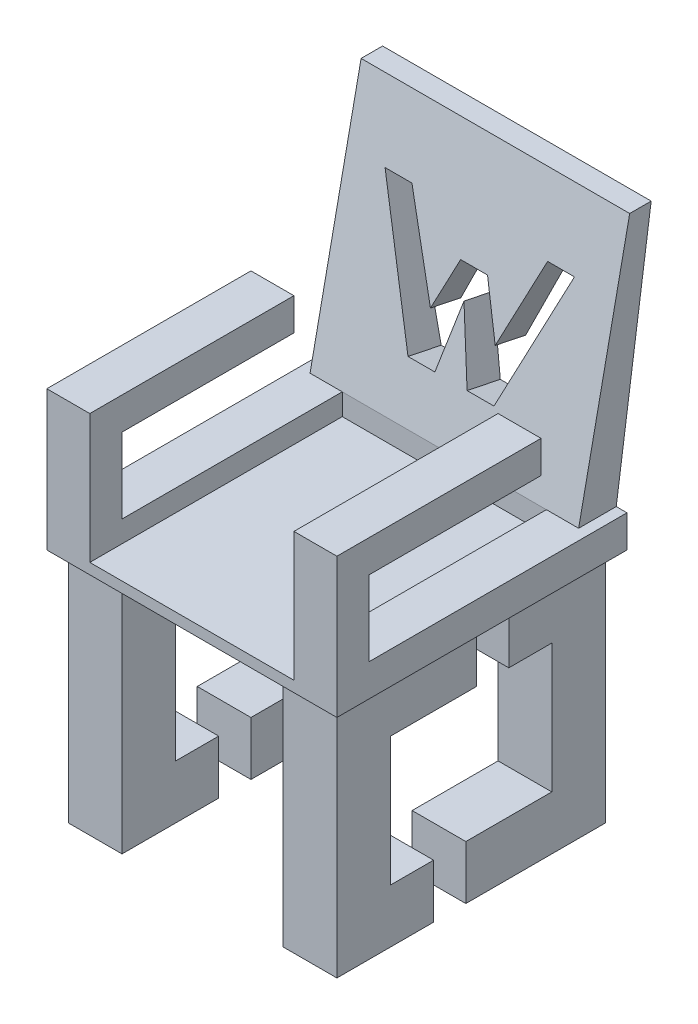
SolidWorks part; units mm, degrees
ref_plane "Front Plane" through (0, 0, 0) normal (0, 0, 1) x (1, 0, 0)
ref_plane "Top Plane" through (0, 0, 0) normal (0, 1, 0) x (1, 0, 0)
ref_plane "Right Plane" through (0, 0, 0) normal (1, 0, 0) x (0, 0, -1)
sketch "Sketch1" plane through (0, 0, 0) normal (1, 0, 0) x (0, 0, -1)
  line L0 (0, 0) -> (228.6, 0)
  line L1 (228.6, 0) -> (228.6, 127)
  line L2 (228.6, 127) -> (127, 127)
  line L3 (127, 127) -> (127, 431.8)
  line L4 (127, 431.8) -> (330.2, 431.8)
  line L5 (330.2, 431.8) -> (330.2, 558.8)
  line L6 (330.2, 558.8) -> (0, 558.8)
  line L7 (0, 558.8) -> (0, 0)
  line L8 (635, 558.8) -> (635, 0)
  line L9 (635, 0) -> (304.8, 0)
  line L10 (304.8, 0) -> (304.8, 127)
  line L11 (304.8, 127) -> (508, 127)
  line L12 (508, 127) -> (508, 431.8)
  line L13 (508, 431.8) -> (406.4, 431.8)
  line L14 (406.4, 431.8) -> (406.4, 558.8)
  line L15 (406.4, 558.8) -> (635, 558.8)
  dimension "D1" = 558.8
  dimension "D2" = 127
  dimension "D3" = 635
  dimension "D4" = 127
  dimension "D5" = 203.2
  dimension "D6" = 101.6
  dimension "D7" = 203.2
  dimension "D8" = 101.6
extrude "Boss-Extrude1" add sketch "Sketch1" along normal blind 127
ref_plane "Plane1" through (635, 0, 0) normal (1, 0, 0) x (0, 0, -1)
ref_plane "Plane3" through (635, 0, 0) normal (1, 0, 0) x (0, 0, -1)
sketch "Sketch9" plane through (635, 0, 0) normal (1, 0, 0) x (0, 0, -1)
  line L0 (127, 431.8) -> (330.2, 431.8)
  line L1 (330.2, 431.8) -> (330.2, 558.8)
  line L2 (330.2, 558.8) -> (0, 558.8)
  line L3 (0, 558.8) -> (0, 0)
  line L4 (0, 0) -> (228.6, 0)
  line L5 (228.6, 0) -> (228.6, 127)
  line L6 (228.6, 127) -> (127, 127)
  line L7 (127, 127) -> (127, 431.8)
  line L8 (406.4, 558.8) -> (406.4, 431.8)
  line L9 (406.4, 431.8) -> (508, 431.8)
  line L10 (508, 431.8) -> (508, 127)
  line L11 (508, 127) -> (304.8, 127)
  line L12 (304.8, 127) -> (304.8, 0)
  line L13 (304.8, 0) -> (635, 0)
  line L14 (635, 0) -> (635, 558.8)
  line L15 (635, 558.8) -> (406.4, 558.8)
extrude "Boss-Extrude7" add sketch "Sketch9" against normal blind 127 separate body
ref_plane "Plane4" through (0, 558.8, 0) normal (0, 1, 0) x (1, 0, 0)
sketch "Sketch10" plane through (0, 558.8, 0) normal (0, 1, 0) x (1, 0, 0)
  line L0 (0, 330.2) -> (0, 0) construction
  line L1 (-25.4, 660.4) -> (660.4, 660.4)
  line L2 (-25.4, 660.4) -> (-25.4, -25.4)
  line L3 (-25.4, -25.4) -> (660.4, -25.4)
  line L4 (660.4, 660.4) -> (660.4, -25.4)
  line L5 (508, 0) -> (635, 0) construction
  dimension "D1" = 685.8
  dimension "D2" = 685.8
  dimension "D3" = 25.4
  dimension "D4" = 25.4
extrude "Boss-Extrude8" add sketch "Sketch10" along normal blind 76.2
sketch "Sketch11" plane through (0, 635, 0) normal (0, 1, 0) x (1, 0, 0)
  line L0 (-25.4, -25.4) -> (660.4, -25.4) construction
  line L1 (76.2, 571.5) -> (558.8, 571.5)
  line L2 (76.2, 571.5) -> (76.2, -25.4)
  line L3 (76.2, -25.4) -> (558.8, -25.4)
  line L4 (558.8, 571.5) -> (558.8, -25.4)
  line L5 (-25.4, 660.4) -> (-25.4, -25.4) construction
  line L6 (660.4, -25.4) -> (660.4, 660.4) construction
  line L7 (660.4, 660.4) -> (-25.4, 660.4) construction
  dimension "D1" = 101.6
  dimension "D2" = 101.6
  dimension "D3" = 88.9
extrude "Cut-Extrude3" cut sketch "Sketch11" against normal blind 50.8
sketch "Sketch13" plane through (635, 0, 0) normal (1, 0, 0) x (0, 0, -1)
  line L0 (660.4, 635) -> (742.9821, 1219.2)
  line L1 (742.9821, 1219.2) -> (692.1821, 1219.2)
  line L2 (692.1821, 1219.2) -> (571.5, 635)
  line L3 (571.5, 635) -> (660.4, 635)
  line L4 (304.8, 0) -> (635, 0) construction
  dimension "D1" = 50.8
  dimension "D2" = 1219.2
extrude "Boss-Extrude9" add sketch "Sketch13" against normal blind 635
ref_plane "Plane5" through (660.4, 0, 0) normal (1, 0, 0) x (0, 0, -1)
sketch "Sketch15" plane through (660.4, 0, 0) normal (1, 0, 0) x (0, 0, -1)
  line L0 (-25.4, 635) -> (-25.4, 889)
  line L1 (-25.4, 889) -> (457.2, 889)
  line L2 (457.2, 889) -> (457.2, 812.8)
  line L3 (457.2, 812.8) -> (50.8, 812.8)
  line L4 (50.8, 812.8) -> (50.8, 635)
  line L5 (-25.4, 635) -> (660.4, 635) construction
  line L6 (50.8, 635) -> (-25.4, 635)
  dimension "D1" = 76.2
  dimension "D2" = 76.2
  dimension "D3" = 482.6
  dimension "D4" = 254
extrude "Boss-Extrude11" add sketch "Sketch15" against normal blind 101.6
ref_plane "Plane6" through (-25.4, 0, 0) normal (1, 0, 0) x (0, 0, -1)
sketch "Sketch16" plane through (-25.4, 0, 0) normal (1, 0, 0) x (0, 0, -1)
  line L0 (50.8, 635) -> (50.8, 812.8)
  line L1 (50.8, 812.8) -> (457.2, 812.8)
  line L2 (457.2, 812.8) -> (457.2, 889)
  line L3 (457.2, 889) -> (-25.4, 889)
  line L4 (-25.4, 889) -> (-25.4, 635)
  line L5 (-25.4, 635) -> (50.8, 635)
extrude "Boss-Extrude12" add sketch "Sketch16" along normal blind 101.6
sketch "Sketch17" plane through (0, -87.2379, -422.3025) normal (0, 0.2023, 0.9793) x (1, 0, 0)
  line L0 (90.0723, 1168.9221) -> (153.5723, 1168.9221)
  line L1 (153.5723, 1168.9221) -> (237.3923, 970.8021)
  line L2 (237.3923, 970.8021) -> (285.75, 1085.1021)
  line L3 (285.75, 1085.1021) -> (349.25, 1085.1021)
  line L4 (349.25, 1085.1021) -> (390.5462, 970.8021)
  line L5 (390.5462, 970.8021) -> (474.3662, 1168.9221)
  line L6 (474.3662, 1168.9221) -> (537.8662, 1168.9221)
  line L7 (537.8662, 1168.9221) -> (409.0668, 864.4872)
  line L8 (409.0668, 864.4872) -> (345.5668, 864.4872)
  line L9 (345.5668, 864.4872) -> (307.4668, 1016.4403)
  line L10 (307.4668, 1016.4403) -> (269.3668, 864.4872)
  line L11 (269.3668, 864.4872) -> (205.8668, 864.4872)
  line L12 (205.8668, 864.4872) -> (90.0723, 1168.9221)
  line L13 (558.8, 737.4872) -> (76.2, 737.4872) construction
  line L14 (0, 1334.0221) -> (0, 737.4872) construction
  line L17 (0, 1334.0221) -> (635, 1334.0221) construction
  point P19 (317.5, 1085.1021)
  dimension "D1" = 63.5
  dimension "D2" = 127
  dimension "D3" = 127
  dimension "D4" = 63.5
  dimension "D5" = 63.5
  dimension "D6" = 38.1
  dimension "D7" = 38.1
  dimension "D8" = 63.5
  dimension "D9" = 63.5
  dimension "D10" = 285.75
  dimension "D11" = 165.1
  dimension "D12" = 165.1
  dimension "D13" = 248.92
  dimension "D14" = 114.3
  dimension "D15" = 114.3
  dimension "D16" = 83.82
  dimension "D17" = 83.82
extrude "Cut-Extrude4" cut sketch "Sketch17" against normal through all
